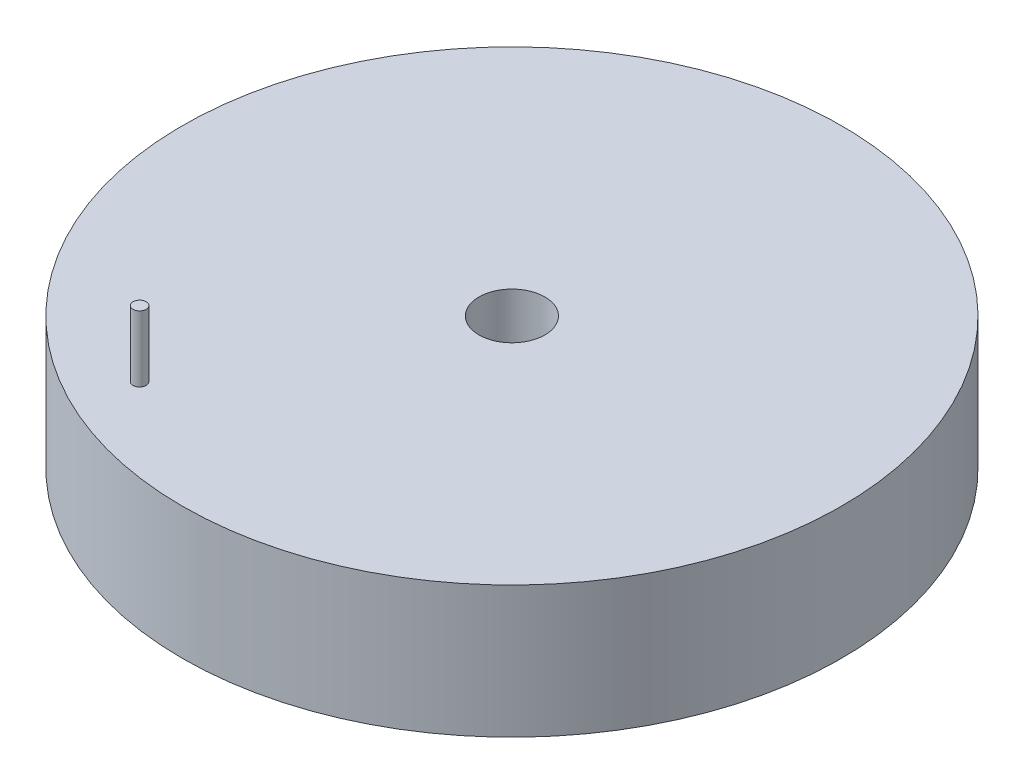
SolidWorks part; units mm, degrees
ref_plane "Front Plane" through (0, 0, 0) normal (0, 0, 1) x (1, 0, 0)
ref_plane "Top Plane" through (0, 0, 0) normal (0, 1, 0) x (1, 0, 0)
ref_plane "Right Plane" through (0, 0, 0) normal (1, 0, 0) x (0, 0, -1)
sketch "Sketch1" plane through (0, 0, 0) normal (0, 1, 0) x (1, 0, 0)
  circle A0 centre (0, 0) radius 50
extrude "Boss-Extrude1" add sketch "Sketch1" along normal blind 20
sketch "Sketch2" plane through (0, 0, 0) normal (0, 1, 0) x (1, 0, 0)
  point P0 (0, 0)
  point P1 (0, 0)
  point P3 (0, 0)
sketch "Sketch3" plane through (0, 20, 0) normal (0, 1, 0) x (1, 0, 0)
  point P0 (0, 0)
sketch "Sketch4" plane through (0, 0, 0) normal (0, -1, 0) x (1, 0, 0)
  circle A0 centre (0, 0) radius 5
extrude "Cut-Extrude2" cut sketch "Sketch4" against normal blind 20
sketch "Sketch5" plane through (0, 20, 0) normal (0, 1, 0) x (1, 0, 0)
  circle A0 centre (-19.6115, -36.8773) radius 1
extrude "Boss-Extrude2" add sketch "Sketch5" along normal blind 10
